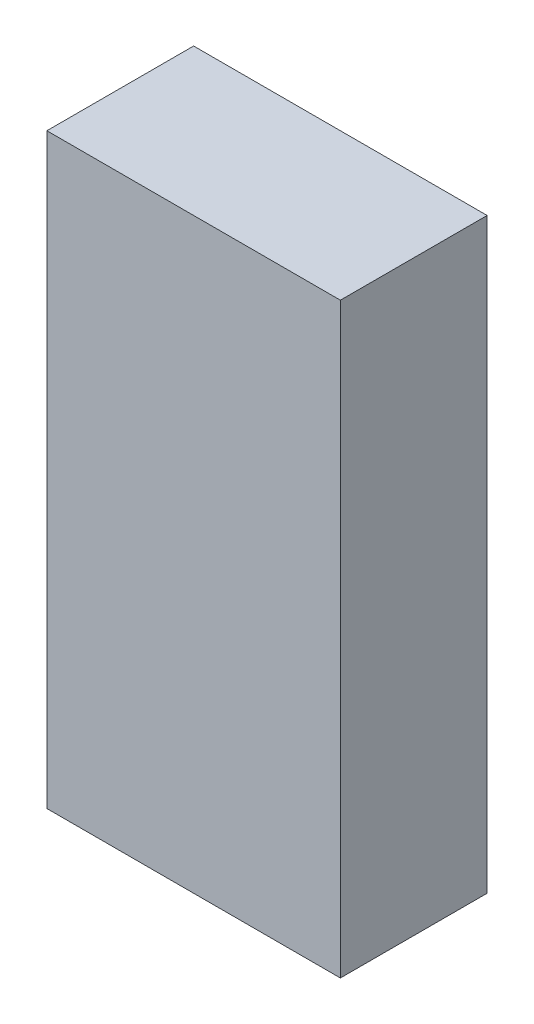
SolidWorks part; units mm, degrees
ref_plane "Front Plane" through (0, 0, 0) normal (0, 0, 1) x (1, 0, 0)
ref_plane "Top Plane" through (0, 0, 0) normal (0, 1, 0) x (1, 0, 0)
ref_plane "Right Plane" through (0, 0, 0) normal (1, 0, 0) x (0, 0, -1)
sketch "Sketch1" plane through (0, 0, 0) normal (0, 1, 0) x (1, 0, 0)
  line L1 (0, 0) -> (10, 0)
  line L2 (0, 0) -> (0, 5)
  line L3 (0, 5) -> (10, 5)
  line L4 (10, 0) -> (10, 5)
  dimension "D1" = 5
  dimension "D2" = 10
extrude "Boss-Extrude1" add sketch "Sketch1" along normal blind 20
